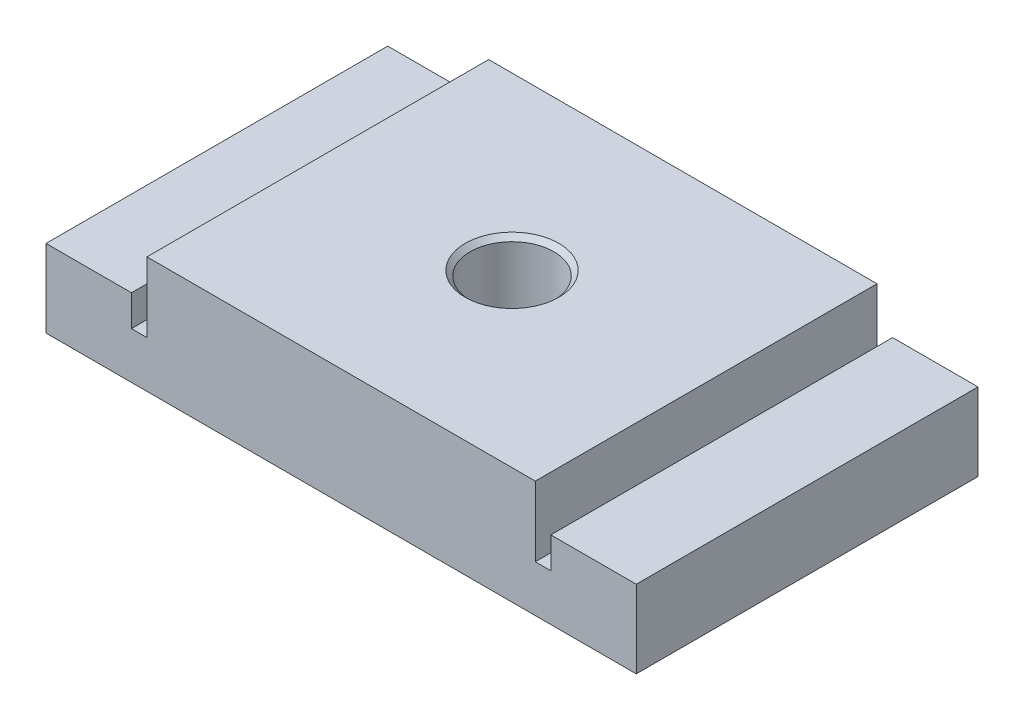
SolidWorks part; units mm, degrees
ref_plane "Front Plane" through (0, 0, 0) normal (0, 0, 1) x (1, 0, 0)
ref_plane "Top Plane" through (0, 0, 0) normal (0, 1, 0) x (1, 0, 0)
ref_plane "Right Plane" through (0, 0, 0) normal (1, 0, 0) x (0, 0, -1)
sketch "Sketch1" plane through (0, 0, 0) normal (0, 0, 1) x (1, 0, 0)
  line L0 (-38, 0) -> (-38, 10)
  line L1 (-38, 10) -> (-27, 10)
  line L2 (-27, 10) -> (-27, 6)
  line L3 (-27, 6) -> (-25, 6)
  line L4 (-25, 6) -> (-25, 15)
  line L5 (0, -55) -> (0, 55) construction
  line L6 (25, 6) -> (25, 15)
  line L7 (27, 6) -> (25, 6)
  line L8 (27, 10) -> (27, 6)
  line L9 (38, 10) -> (27, 10)
  line L10 (38, 0) -> (38, 10)
  line L11 (-25, 15) -> (25, 15)
  line L12 (-38, 0) -> (38, 0)
  dimension "D1" = 76
  dimension "D2" = 50
  dimension "D3" = 2
  dimension "D4" = 15
  dimension "D5" = 9
  dimension "D6" = 10
extrude "Boss-Extrude1" add sketch "Sketch1" along normal mid plane 44
hole_wizard "M12x1.25 Tapped Hole1" positions "Sketch2" profile "Sketch3" tap size "M12x1.25" standard "ANSI Metric" end condition up to next
sketch "Sketch2" plane through (0, 15, 0) normal (0, 1, 0) x (1, 0, 0)
  point P0 (0, 0)
  point P4 (0, 0)
sketch "Sketch3" plane through (0, 15, 0) normal (1, 0, 0) x (0, 0, 1)
  line L0 (0, 0) -> (0, 15)
  line L1 (0, 15) -> (5.4, 15)
  line L2 (5.4, 15) -> (5.4, 0.625)
  line L3 (5.4, 0.625) -> (6.025, 0)
  line L5 (6.025, 0) -> (0, 0)
  line L6 (-5.4, 0.625) -> (-6.025, 0) construction
  line L11 (0, -6.35) -> (0, 107.95) construction
  dimension "Thru Tap Drill Dia." = 10.8
  dimension "Thru Tap Drill Depth" = 15
  dimension "Near C'Sink Dia." = 12.05
  dimension "Near C'Sink Angle" = 90
cosmetic thread "Hole Thread1"
